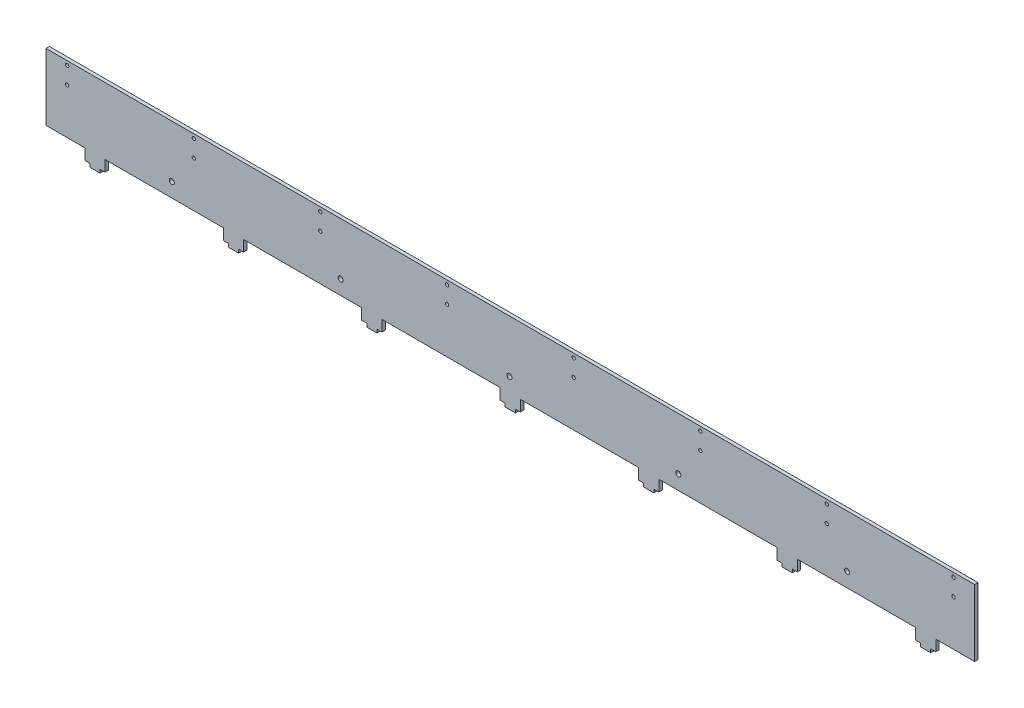
SolidWorks part; units mm, degrees
ref_plane "Спереди" through (0, 0, 0) normal (0, 0, 1) x (1, 0, 0)
ref_plane "Сверху" through (0, 0, 0) normal (0, 1, 0) x (1, 0, 0)
ref_plane "Справа" through (0, 0, 0) normal (1, 0, 0) x (0, 0, -1)
sketch "Эскиз1" plane through (0, 0, 0) normal (0, 0, 1) x (1, 0, 0)
  line L1 (-550, -46) -> (550, -46)
  line L2 (-550, -46) -> (-550, 46)
  line L3 (-550, 46) -> (550, 46)
  line L4 (550, -46) -> (550, 46)
  line L5 (0, 46) -> (0, -46) construction
  line L6 (-550, 0) -> (550, 0) construction
  point P0 (0, 0)
  dimension "D1" = 92
  dimension "D2" = 1100
extrude "Бобышка-Вытянуть1" add sketch "Эскиз1" along normal mid plane 4
sketch "Эскиз2" plane through (0, 0, 2) normal (0, 0, 1) x (1, 0, 0)
  line L0 (-550, -46) -> (550, -46) construction
  line L1 (-550, -46) -> (-504, -46)
  line L2 (-550, -46) -> (-550, -33)
  line L3 (-550, -33) -> (-504, -33)
  line L4 (-504, -46) -> (-504, -33)
  line L5 (550, -46) -> (504, -46)
  line L6 (550, -46) -> (550, -33)
  line L7 (550, -33) -> (504, -33)
  line L8 (504, -46) -> (504, -33)
  line L9 (-480, -33) -> (-340, -33)
  line L10 (-480, -33) -> (-480, -46)
  line L11 (-480, -46) -> (-340, -46)
  line L12 (-340, -33) -> (-340, -46)
  line L14 (-316, -33) -> (-176, -33)
  line L15 (-316, -33) -> (-316, -46)
  line L16 (-316, -46) -> (-176, -46)
  line L17 (-176, -33) -> (-176, -46)
  line L18 (-152, -33) -> (-12, -33)
  line L19 (-152, -33) -> (-152, -46)
  line L20 (-152, -46) -> (-12, -46)
  line L21 (-12, -33) -> (-12, -46)
  line L22 (12, -33) -> (152, -33)
  line L23 (12, -33) -> (12, -46)
  line L24 (12, -46) -> (152, -46)
  line L25 (152, -33) -> (152, -46)
  line L26 (176, -33) -> (316, -33)
  line L27 (176, -33) -> (176, -46)
  line L28 (176, -46) -> (316, -46)
  line L29 (316, -33) -> (316, -46)
  line L30 (340, -33) -> (480, -33)
  line L31 (340, -33) -> (340, -46)
  line L32 (340, -46) -> (480, -46)
  line L33 (480, -33) -> (480, -46)
  point P20 (-316, -39.5)
  point P25 (-152, -39.5)
  point P26 (152, -39.5)
  point P39 (340, -39.5)
  dimension "D1" = 13
  dimension "D5" = 24
  dimension "D6" = 140
  dimension "D7" = 24
  dimension "D2" = 24
  dimension "D3" = 140
  dimension "D4" = 140
  dimension "D8" = 24
  dimension "D9" = 140
  dimension "D10" = 24
  dimension "D11" = 140
  dimension "D12" = 24
  dimension "D13" = 140
  dimension "D14" = 24
extrude "Вырез-Вытянуть1" cut sketch "Эскиз2" against normal through all
sketch "Эскиз3" plane through (0, 0, 2) normal (0, 0, 1) x (1, 0, 0)
  line L0 (550, 46) -> (-550, 46) construction
  line L1 (-550, 46) -> (-550, -33) construction
  circle A0 centre (-525, 41) radius 2
  circle A1 centre (-525, 21) radius 2
  dimension "D1" = 4
  dimension "D2" = 5
  dimension "D3" = 20
  dimension "D4" = 25
extrude "Вырез-Вытянуть2" cut sketch "Эскиз3" against normal through all
pattern_linear "Линейный массив1" count 8 spacing 150 along (1, 0, 0) of "Вырез-Вытянуть2"
sketch "Эскиз4" plane through (0, 0, -2) normal (0, 0, -1) x (-1, 0, 0)
  circle A1 centre (-399, -16) radius 3
  circle A2 centre (-399, -16) radius 3
  dimension "D1" = 0
extrude "Вырез-Вытянуть3" cut sketch "Эскиз4" against normal through all
pattern_linear "Линейный массив2" count 5 spacing 200 along (-1, 0, 0) of "Вырез-Вытянуть3"
sketch "Эскиз5" plane through (0, -46, 0) normal (0, -1, 0) x (1, 0, 0)
  line L0 (492, -2) -> (492, 2) construction
  line L1 (480, 2) -> (504, 2) construction
  line L2 (328, -2) -> (328, 2) construction
  line L3 (316, -2) -> (340, -2) construction
  line L4 (504, 2) -> (480, 2)
  line L5 (480, 2) -> (480, -2)
  line L6 (480, -2) -> (504, -2)
  line L7 (504, -2) -> (504, 2)
  line L8 (498, 2) -> (486, 2)
  line L9 (486, 2) -> (486, -2)
  line L10 (486, -2) -> (498, -2)
  line L11 (498, -2) -> (498, 2)
  line L12 (316, 2) -> (340, 2) construction
  line L13 (164, -2) -> (164, 2) construction
  line L14 (316, -2) -> (340, -2)
  line L15 (340, -2) -> (340, 2)
  line L16 (340, 2) -> (316, 2)
  line L17 (316, 2) -> (316, -2)
  line L18 (322, -2) -> (334, -2)
  line L19 (334, -2) -> (334, 2)
  line L20 (334, 2) -> (322, 2)
  line L21 (322, 2) -> (322, -2)
  line L22 (152, -2) -> (176, -2) construction
  line L23 (152, 2) -> (176, 2) construction
  line L24 (0, -2) -> (0, 2) construction
  line L25 (176, 2) -> (152, 2)
  line L26 (152, 2) -> (152, -2)
  line L27 (152, -2) -> (176, -2)
  line L28 (176, -2) -> (176, 2)
  line L29 (170, 2) -> (158, 2)
  line L30 (158, 2) -> (158, -2)
  line L31 (158, -2) -> (170, -2)
  line L32 (170, -2) -> (170, 2)
  line L33 (-12, -2) -> (12, -2) construction
  line L34 (-12, 2) -> (12, 2) construction
  line L36 (-12, -2) -> (12, -2)
  line L37 (12, -2) -> (12, 2)
  line L38 (12, 2) -> (-12, 2)
  line L39 (-12, 2) -> (-12, -2)
  line L40 (-6, -2) -> (6, -2)
  line L41 (6, -2) -> (6, 2)
  line L42 (6, 2) -> (-6, 2)
  line L43 (-6, 2) -> (-6, -2)
  line L44 (-480, 2) -> (-504, 2) construction
  line L46 (-504, -2) -> (-480, -2) construction
  line L48 (-316, 2) -> (-340, 2) construction
  line L50 (-340, -2) -> (-316, -2) construction
  line L52 (-152, 2) -> (-176, 2) construction
  line L54 (-176, -2) -> (-152, -2) construction
  line L56 (-486, 2) -> (-498, 2)
  line L57 (-498, 2) -> (-498, -2)
  line L58 (-498, -2) -> (-486, -2)
  line L59 (-486, -2) -> (-486, 2)
  line L60 (-322, 2) -> (-334, 2)
  line L61 (-334, 2) -> (-334, -2)
  line L62 (-334, -2) -> (-322, -2)
  line L63 (-322, -2) -> (-322, 2)
  line L64 (-158, 2) -> (-170, 2)
  line L65 (-170, 2) -> (-170, -2)
  line L66 (-170, -2) -> (-158, -2)
  line L67 (-158, -2) -> (-158, 2)
  line L68 (-492, -2) -> (-492, 2) construction
  line L69 (-504, 2) -> (-480, 2) construction
  line L70 (-328, -2) -> (-328, 2) construction
  line L71 (-340, 2) -> (-316, 2) construction
  line L72 (-164, -2) -> (-164, 2) construction
  line L73 (-176, 2) -> (-152, 2) construction
  point P85 (-334, 0)
  dimension "D2" = 12
  dimension "D4" = 12
  dimension "D6" = 12
  dimension "D8" = 12
  dimension "D9" = 12
  dimension "D10" = 12
  dimension "D11" = 12
  dimension "D1" = 0
  dimension "D3" = 0
  dimension "D5" = 0
  dimension "D7" = 0
extrude "Бобышка-Вытянуть2" add sketch "Эскиз5" along normal blind 4
equation "\"D7@Эскиз2\"=\"D5@Эскиз2\""
equation "\"D2@Эскиз2\"=\"D5@Эскиз2\""
equation "\"D3@Эскиз2\"=\"D6@Эскиз2\""
equation "\"D4@Эскиз2\"=\"D6@Эскиз2\""
equation "\"D8@Эскиз2\"=\"D5@Эскиз2\""
equation "\"D9@Эскиз2\"=\"D6@Эскиз2\""
equation "\"D10@Эскиз2\"=\"D5@Эскиз2\""
equation "\"D11@Эскиз2\"=\"D6@Эскиз2\""
equation "\"D12@Эскиз2\"=\"D5@Эскиз2\""
equation "\"D13@Эскиз2\"=\"D6@Эскиз2\""
equation "\"D14@Эскиз2\"=\"D5@Эскиз2\""
